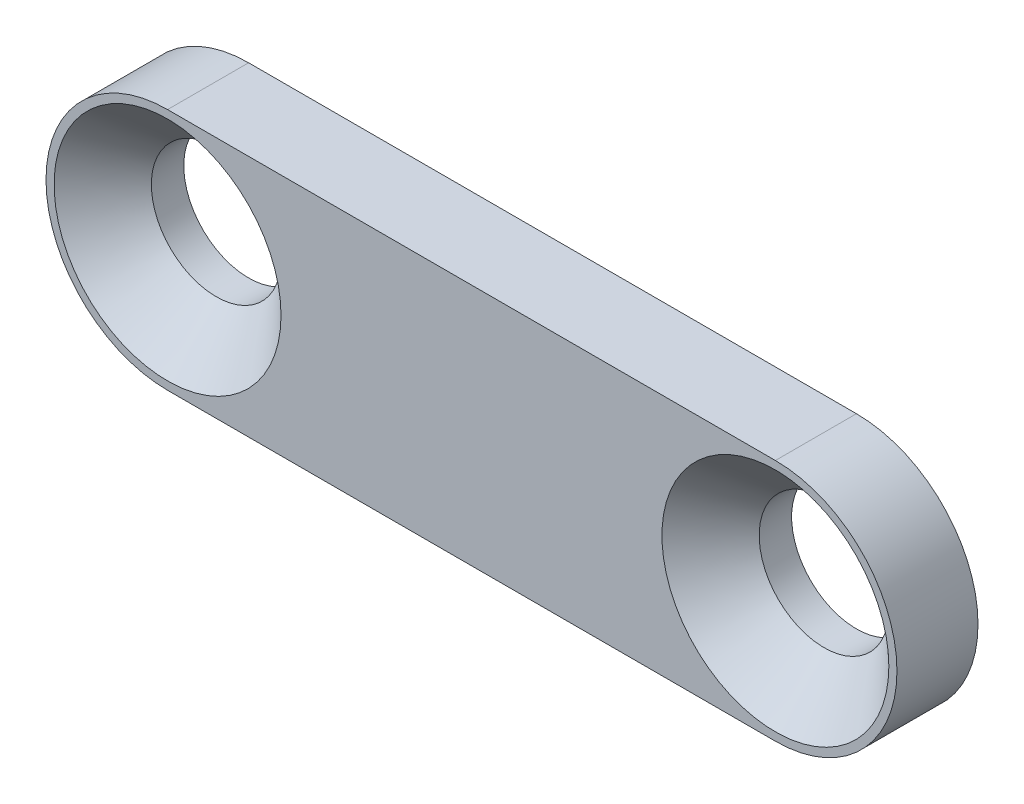
SolidWorks part; units mm, degrees
ref_plane "前视基准面" through (0, 0, 0) normal (0, 0, 1) x (1, 0, 0)
ref_plane "上视基准面" through (0, 0, 0) normal (0, 1, 0) x (1, 0, 0)
ref_plane "右视基准面" through (0, 0, 0) normal (1, 0, 0) x (0, 0, -1)
other "Configuration Table"
sketch "草图1" plane through (0, 0, 0) normal (0, 0, 1) x (1, 0, 0)
  line L0 (0, 0) -> (-15, 0) construction
  line L1 (0, -3) -> (-15, -3)
  line L2 (0, 3) -> (-15, 3)
  arc A0 (0, -3) -> (0, 3) centre (0, 0) ccw
  arc A1 (-15, 3) -> (-15, -3) centre (-15, 0) ccw
  point P3 (-7.5, 0)
  dimension "D2" = 6
  dimension "D1" = 15
extrude "凸台-拉伸1" add sketch "草图1" along normal blind 2
sketch "草图2" plane through (0, 0, 2) normal (0, 0, 1) x (1, 0, 0)
  circle A0 centre (0, 0) radius 1.6
  circle A1 centre (-15, 0) radius 1.6
  dimension "D1" = 3.2
extrude "切除-拉伸1" cut sketch "草图2" against normal through all
chamfer "倒角1" distance 1.2 angle 45 2 edges at (1.6, 0, 2) (-13.4, 0, 2)
